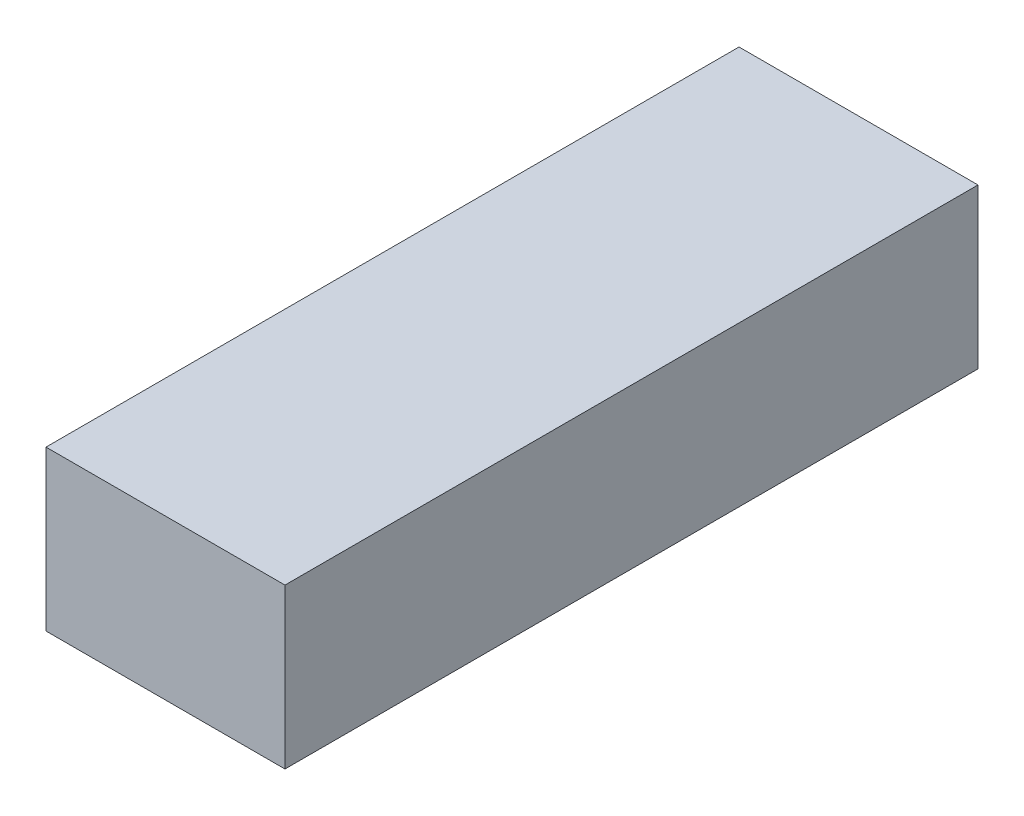
SolidWorks part; units mm, degrees
ref_plane "Piano frontale" through (0, 0, 0) normal (0, 0, 1) x (1, 0, 0)
ref_plane "Piano superiore" through (0, 0, 0) normal (0, 1, 0) x (1, 0, 0)
ref_plane "Piano destro" through (0, 0, 0) normal (1, 0, 0) x (0, 0, -1)
sketch "Schizzo1" plane through (0, 0, 0) normal (0, 0, 1) x (1, 0, 0)
  line L1 (-15, -10) -> (15, -10)
  line L2 (-15, -10) -> (-15, 10)
  line L3 (-15, 10) -> (15, 10)
  line L4 (15, -10) -> (15, 10)
  line L5 (-15, -10) -> (15, 10) construction
  line L6 (-15, 10) -> (15, -10) construction
  point P0 (0, 0)
  dimension "D1" = 30
  dimension "D2" = 20
extrude "Estrusione-Estrusione1" add sketch "Schizzo1" along normal blind 87
